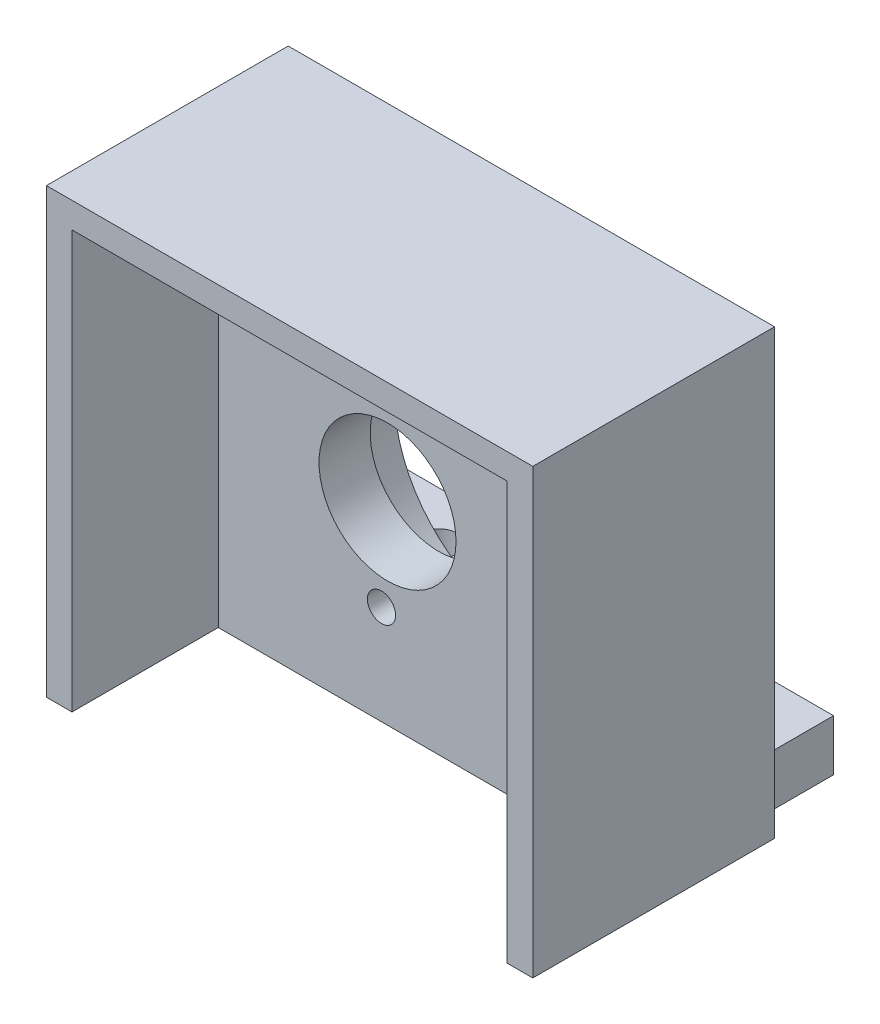
SolidWorks part; units mm, degrees
ref_plane "Front Plane" through (0, 0, 0) normal (0, 0, 1) x (1, 0, 0)
ref_plane "Top Plane" through (0, 0, 0) normal (0, 1, 0) x (1, 0, 0)
ref_plane "Right Plane" through (0, 0, 0) normal (1, 0, 0) x (0, 0, -1)
sketch "Sketch1" plane through (0, 0, 0) normal (0, 0, 1) x (1, 0, 0)
  line L0 (-6.75, 11.6913) -> (0, 0) construction
  line L1 (0, 0) -> (13.5, 0) construction
  line L3 (-24, 24) -> (24, 24)
  line L4 (-24, 24) -> (-24, -24)
  line L5 (-24, -24) -> (24, -24)
  line L6 (24, 24) -> (24, -24)
  circle A0 centre (0, 0) radius 13.5 construction
  circle A1 centre (13.5, 0) radius 1.75
  circle A2 centre (-6.75, 11.6913) radius 1.75
  circle A3 centre (-6.75, -11.6913) radius 1.75
  circle A4 centre (-6, 0) radius 8.5
  point P13 (0, -24)
  point P15 (-24, 0)
  dimension "D1" = 27
  dimension "D3" = 3.5
  dimension "D5" = 17
  dimension "D2" = 120
  dimension "D4" = 24
  dimension "D6" = 6
extrude "Boss-Extrude2" add sketch "Sketch1" along normal mid plane 6.35
sketch "Sketch2" plane through (24, 0, 0) normal (1, 0, 0) x (0, 0, -1)
  line L1 (3.175, -24) -> (17.175, -24)
  line L2 (3.175, -24) -> (3.175, -17.65)
  line L3 (3.175, -17.65) -> (17.175, -17.65)
  line L4 (17.175, -24) -> (17.175, -17.65)
  dimension "D1" = 14
  dimension "D2" = 6.35
extrude "Boss-Extrude3" add sketch "Sketch2" against normal up to surface (48 mm away) up to face at (-24, 0, 0)
sketch "Sketch3" plane through (0, 0, 3.175) normal (0, 0, 1) x (1, 0, 0)
  line L4 (-24, 24) -> (-24, -24)
  line L5 (-24, -24) -> (24, -24)
  line L6 (24, -24) -> (24, 24)
  line L7 (24, 24) -> (-24, 24)
  line L8 (-24, 24) -> (-24, -24)
  line L10 (24, -24) -> (24, 24)
  line L11 (24, 24) -> (-24, 24)
  line L12 (-24, -24) -> (24, -24)
  circle A0 centre (0, 0) radius 17
  dimension "D1" = 34
  dimension "D2" = 0
extrude "Boss-Extrude4" add sketch "Sketch3" along normal blind 5.5
mirror "Mirror1" about plane through (0, 0, 0) normal (0, 0, 1) of "Boss-Extrude4", "Boss-Extrude3"
sketch "Sketch4" plane through (0, -17.65, 0) normal (0, 1, 0) x (1, 0, 0)
  line L0 (-24, -17.175) -> (24, -17.175) construction
  line L1 (16, -13.175) -> (-16, -13.175)
  line L2 (16, -13.175) -> (16, 13.175)
  line L3 (16, 13.175) -> (-16, 13.175)
  line L4 (-16, -13.175) -> (-16, 13.175)
  line L5 (16, -13.175) -> (-16, 13.175) construction
  line L6 (16, 13.175) -> (-16, -13.175) construction
  point P0 (0, 0)
  dimension "D1" = 4
  dimension "D2" = 32
hole_wizard "M4 Clearance Hole1" positions "Sketch5" profile "Sketch6" hole size "M4" standard "ANSI Metric" end condition through all
sketch "Sketch5" plane through (0, -17.65, 0) normal (0, 1, 0) x (1, 0, 0)
  point P0 (-16, -13.175)
  point P3 (16, -13.175)
  point P6 (16, 13.175)
  point P9 (-16, 13.175)
sketch "Sketch6" plane through (-16, -17.65, 13.175) normal (1, 0, 0) x (0, 0, 1)
  line L0 (0, 0) -> (0, 6.35)
  line L1 (0, 6.35) -> (2.25, 6.35)
  line L2 (2.25, 6.35) -> (2.25, 0)
  line L5 (2.25, 0) -> (0, 0)
  line L11 (0, -6.35) -> (0, 107.95) construction
  dimension "Thru Hole Dia." = 4.5
  dimension "Thru Hole Depth" = 6.35
sketch "Sketch7" plane through (0, 0, 17.175) normal (0, 0, 1) x (1, 0, 0)
  line L4 (24, -17.65) -> (-24, -17.65)
  line L5 (-24, -17.65) -> (-24, -24)
  line L6 (-24, -24) -> (24, -24)
  line L7 (24, -24) -> (24, -17.65)
  line L8 (24, -17.65) -> (-24, -17.65)
  line L9 (-24, -17.65) -> (-24, -24)
  line L10 (-24, -24) -> (24, -24)
  line L11 (24, -24) -> (24, -17.65)
  dimension "D1" = 0
extrude "Boss-Extrude5" add sketch "Sketch7" along normal blind 2
mirror "Mirror2" about plane through (0, 0, 0) normal (0, 0, 1) of "Boss-Extrude5"
sketch "Sketch8" plane through (-24, 0, 0) normal (-1, 0, 0) x (0, 0, 1)
  line L6 (-19.175, -17.65) -> (-19.175, -24)
  line L8 (-8.675, -17.65) -> (-19.175, -17.65)
  line L9 (-19.175, -17.65) -> (-19.175, -24)
  line L10 (-19.175, -24) -> (19.175, -24)
  line L12 (19.175, -24) -> (19.175, -17.65)
  line L13 (8.675, -17.65) -> (8.675, 24)
  line L14 (8.675, 24) -> (-8.675, 24)
  line L16 (-8.675, -17.65) -> (-19.175, -17.65)
  line L18 (-19.175, -24) -> (19.175, -24)
  line L21 (8.675, -17.65) -> (8.675, 24)
  line L22 (8.675, 24) -> (-8.675, 24)
  line L25 (19.175, -24) -> (19.175, -17.65)
  line L26 (19.175, -17.65) -> (8.675, -17.65)
  line L27 (19.175, -17.65) -> (8.675, -17.65)
  line L28 (-8.675, 24) -> (-8.675, -17.65)
  line L29 (-8.675, 24) -> (-8.675, -17.65)
  dimension "D1" = 0
extrude "Boss-Extrude6" add sketch "Sketch8" along normal blind 3
mirror "Mirror3" about plane through (0, 0, 0) normal (1, 0, 0) of "Boss-Extrude6"
sketch "Sketch12" plane through (0, 0, 19.175) normal (0, 0, 1) x (1, 0, 0)
  line L1 (-27, -24) -> (27, -24)
  line L2 (-27, -24) -> (-27, 24)
  line L3 (-27, 24) -> (27, 24)
  line L4 (27, -24) -> (27, 24)
extrude "Cut-Extrude4" cut sketch "Sketch12" against normal up to surface (16 mm away) up to face at (2.5, 0, 3.175)
sketch "Sketch13" plane through (0, 24, 0) normal (0, 1, 0) x (1, 0, 0)
  line L4 (-27, -3.175) -> (27, -3.175)
  line L5 (27, -3.175) -> (27, 8.675)
  line L6 (27, 8.675) -> (-27, 8.675)
  line L7 (-27, 8.675) -> (-27, -3.175)
  line L8 (-27, -3.175) -> (27, -3.175)
  line L9 (27, -3.175) -> (27, 8.675)
  line L10 (27, 8.675) -> (-27, 8.675)
  line L11 (-27, 8.675) -> (-27, -3.175)
  dimension "D1" = 0
extrude "Boss-Extrude7" [suppressed] add sketch "Sketch13" along normal offset from surface (40.9 mm away) 88.9
sketch "Sketch15" plane through (0, 0, -8.675) normal (0, 0, -1) x (-1, 0, 0)
  line L0 (30.175, -24) -> (30.175, 24)
  line L1 (-30.175, 24) -> (-30.175, -24)
  line L2 (30.175, -24) -> (27, -24)
  line L3 (30.175, 24) -> (-30.175, 24)
  line L4 (27, -24) -> (27, 24)
  line L5 (-27, -24) -> (27, -24)
  line L6 (-27, 24) -> (-27, -24)
  line L7 (27, 24) -> (-27, 24)
  line L8 (27, -24) -> (27, 24)
  line L10 (-27, 24) -> (-27, -24)
  line L11 (27, 24) -> (-27, 24)
  line L12 (30.175, 24) -> (30.175, 17.65)
  line L13 (30.175, 17.65) -> (-30.175, 17.65)
  line L14 (-30.175, 24) -> (-30.175, 17.65)
  line L15 (-27, -24) -> (-30.175, -24)
  line L16 (30.175, 20.825) -> (-30.175, 20.825)
  line M11 (27, -17.65) -> (27, 24)
  dimension "D3" = 3.175
  dimension "D4" = 3.175
  dimension "D1" = 0
  dimension "D2" = 3.175
extrude "Boss-Extrude8" add sketch "Sketch15" against normal blind 30 contours L0 L13 L8 L2 M11 | L15 L10 L13 L1 | L10 L16 L14 L13 | L8 L16 L10 L13 | L0 L16 L8 L13
sketch "Sketch16" plane through (0, 0, 3.175) normal (0, 0, 1) x (1, 0, 0)
  line L4 (-27, 20.825) -> (27, 20.825)
  line L5 (27, 20.825) -> (27, 24)
  line L6 (27, 24) -> (-27, 24)
  line L7 (-27, 24) -> (-27, 20.825)
  line L8 (-27, 20.825) -> (27, 20.825)
  line L9 (27, 20.825) -> (27, 24)
  line L10 (27, 24) -> (-27, 24)
  line L11 (-27, 24) -> (-27, 20.825)
  dimension "D1" = 0
extrude "Cut-Extrude5" cut sketch "Sketch16" against normal through all
sketch "Sketch17" plane through (0, 20.825, 0) normal (0, 1, 0) x (1, 0, 0)
  line L4 (30.175, -21.325) -> (30.175, 8.675)
  line L5 (30.175, 8.675) -> (-30.175, 8.675)
  line L6 (-30.175, 8.675) -> (-30.175, -21.325)
  line L7 (-30.175, -21.325) -> (30.175, -21.325)
  line L8 (30.175, -21.325) -> (30.175, 8.675)
  line L9 (30.175, 8.675) -> (-30.175, 8.675)
  line L10 (-30.175, 8.675) -> (-30.175, -21.325)
  line L11 (-30.175, -21.325) -> (30.175, -21.325)
  dimension "D1" = 0
extrude "Boss-Extrude9" add sketch "Sketch17" along normal blind 10.16
sketch "Sketch18" plane through (0, 0, 21.325) normal (0, 0, 1) x (1, 0, 0)
  line L0 (27, 17.65) -> (27, -24) construction
  line L1 (-27, 17.65) -> (27, 17.65)
  line L2 (-27, 17.65) -> (-27, 27.81)
  line L3 (-27, 27.81) -> (27, 27.81)
  line L4 (27, 17.65) -> (27, 27.81)
  line L5 (-30.175, 30.985) -> (30.175, 30.985) construction
  dimension "D1" = 3.175
extrude "Cut-Extrude6" cut sketch "Sketch18" against normal up to surface (18.15 mm away) up to face at (2.5, 0, 3.175)
